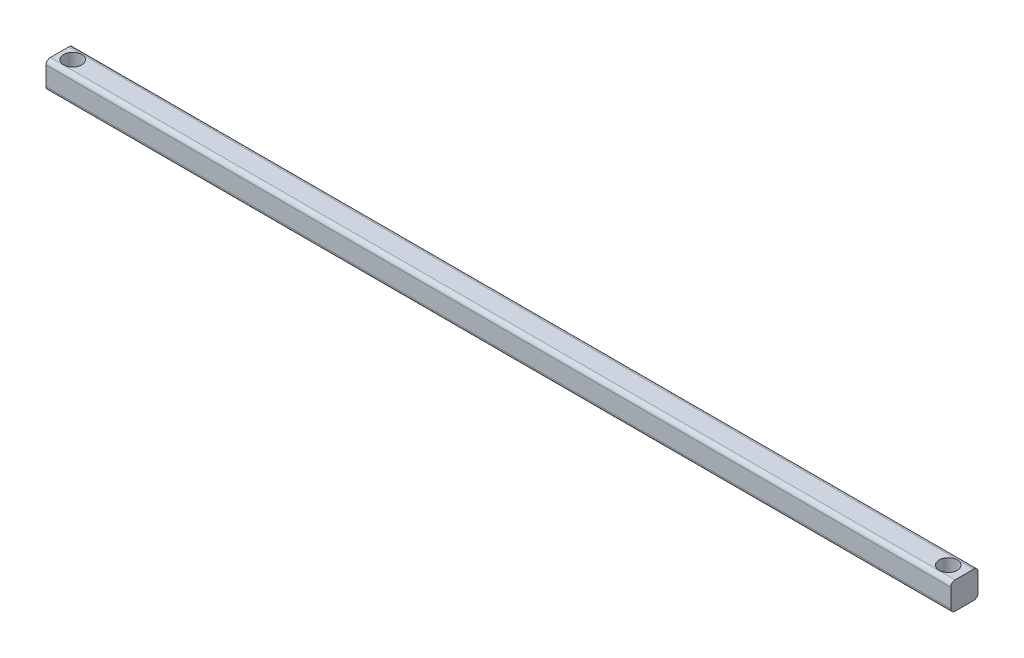
SolidWorks part; units mm, degrees
ref_plane "前视基准面" through (0, 0, 0) normal (0, 0, 1) x (1, 0, 0)
ref_plane "上视基准面" through (0, 0, 0) normal (0, 1, 0) x (1, 0, 0)
ref_plane "右视基准面" through (0, 0, 0) normal (1, 0, 0) x (0, 0, -1)
sketch "草图1" plane through (0, 0, 0) normal (1, 0, 0) x (0, 0, -1)
  line L1 (-3.16, -3.16) -> (3.16, -3.16)
  line L2 (-3.16, -3.16) -> (-3.16, 3.16)
  line L3 (-3.16, 3.16) -> (3.16, 3.16)
  line L4 (3.16, -3.16) -> (3.16, 3.16)
  line L5 (-3.16, -3.16) -> (3.16, 3.16) construction
  line L6 (-3.16, 3.16) -> (3.16, -3.16) construction
  point P0 (0, 0)
  dimension "D1" = 6.32
  dimension "D2" = 6.32
extrude "凸台-拉伸1" add sketch "草图1" along normal blind 210
sketch "草图2" plane through (0, 3.16, 0) normal (0, 1, 0) x (1, 0, 0)
  circle A0 centre (3.0433, 0) radius 2.1
  circle A1 centre (206.2433, 0) radius 2.1
  dimension "D1" = 4.2
  dimension "D2" = 203.2
extrude "切除-拉伸1" cut sketch "草图2" against normal blind 210
fillet "圆角1" radius 1 4 edges at (105, -3.16, -3.16) (105, -3.16, 3.16) (105, 3.16, -3.16) (105, 3.16, 3.16)
